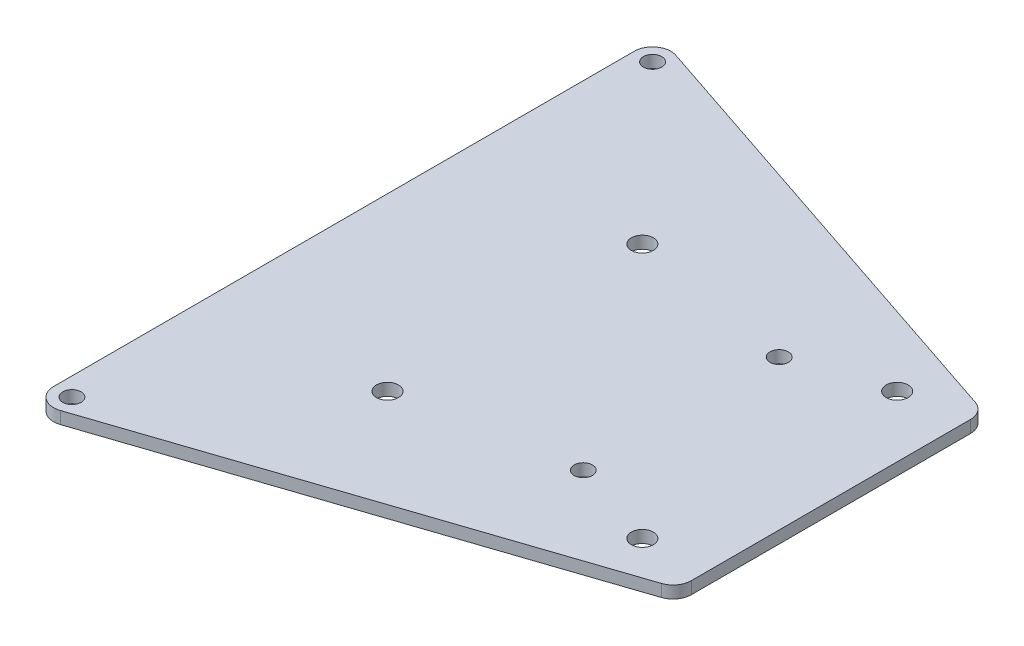
SolidWorks part; units mm, degrees
ref_plane "Front Plane" through (0, 0, 0) normal (0, 0, 1) x (1, 0, 0)
ref_plane "Top Plane" through (0, 0, 0) normal (0, 1, 0) x (1, 0, 0)
ref_plane "Right Plane" through (0, 0, 0) normal (1, 0, 0) x (0, 0, -1)
sketch "Croquis1" plane through (0, 0, 0) normal (0, 1, 0) x (1, 0, 0)
  line L0 (0, 0) -> (0, -95.05) construction
  line L1 (0.9525, 2.8448) -> (74.6725, -21.8394)
  line L2 (76.72, -24.6842) -> (76.72, -70.3658)
  line L3 (74.6725, -73.2106) -> (0.9525, -97.8948)
  line L4 (-3, -95.05) -> (-3, 0)
  circle A0 centre (25, -26.675) radius 1.8
  circle A1 centre (25, -68.395) radius 1.8
  circle A2 centre (66.72, -26.675) radius 1.8
  circle A3 centre (66.72, -68.395) radius 1.8
  circle A4 centre (0, 0) radius 1.5
  circle A5 centre (0, -95.05) radius 1.5
  circle A6 centre (52.22, -31.49) radius 1.5
  circle A7 centre (52.22, -63.56) radius 1.5
  arc A8 (0.9525, -97.8948) -> (-3, -95.05) centre (0, -95.05) cw
  arc A9 (-3, 0) -> (0.9525, 2.8448) centre (0, 0) cw
  arc A10 (76.72, -70.3658) -> (74.6725, -73.2106) centre (73.72, -70.3658) cw
  arc A11 (74.6725, -21.8394) -> (76.72, -24.6842) centre (73.72, -24.6842) cw
  circle A12 centre (29, -70.925) radius 1.75
  circle A13 centre (29, -24.125) radius 1.75
  circle A14 centre (61, -47.525) radius 1.75
  point P17 (0, -47.525)
  point P24 (76.72, -47.525)
  point P33 (-3, -47.525)
  point P36 (76.72, -72.525)
  point P39 (76.72, -22.525)
  dimension "D3" = 3.6
  dimension "D4" = 3
  dimension "D11" = 3
  dimension "D14" = 3
  dimension "D16" = 3.5
  dimension "D1" = 41.72
  dimension "D2" = 41.72
  dimension "D5" = 95.05
  dimension "D6" = 52.22
  dimension "D7" = 32.07
  dimension "D8" = 16.035
  dimension "D9" = 20.85
  dimension "D10" = 25
  dimension "D12" = 50
  dimension "D13" = 10
  dimension "D15" = 46.8
  dimension "D17" = 23.4
  dimension "D18" = 32
  dimension "D19" = 32
extrude "Saliente-Extruir1" add sketch "Croquis1" along normal blind 2
equation "\"D8@Croquis1\"=32.07/2"
equation "\"D17@Croquis1\"=\"D15@Croquis1\"/2"
